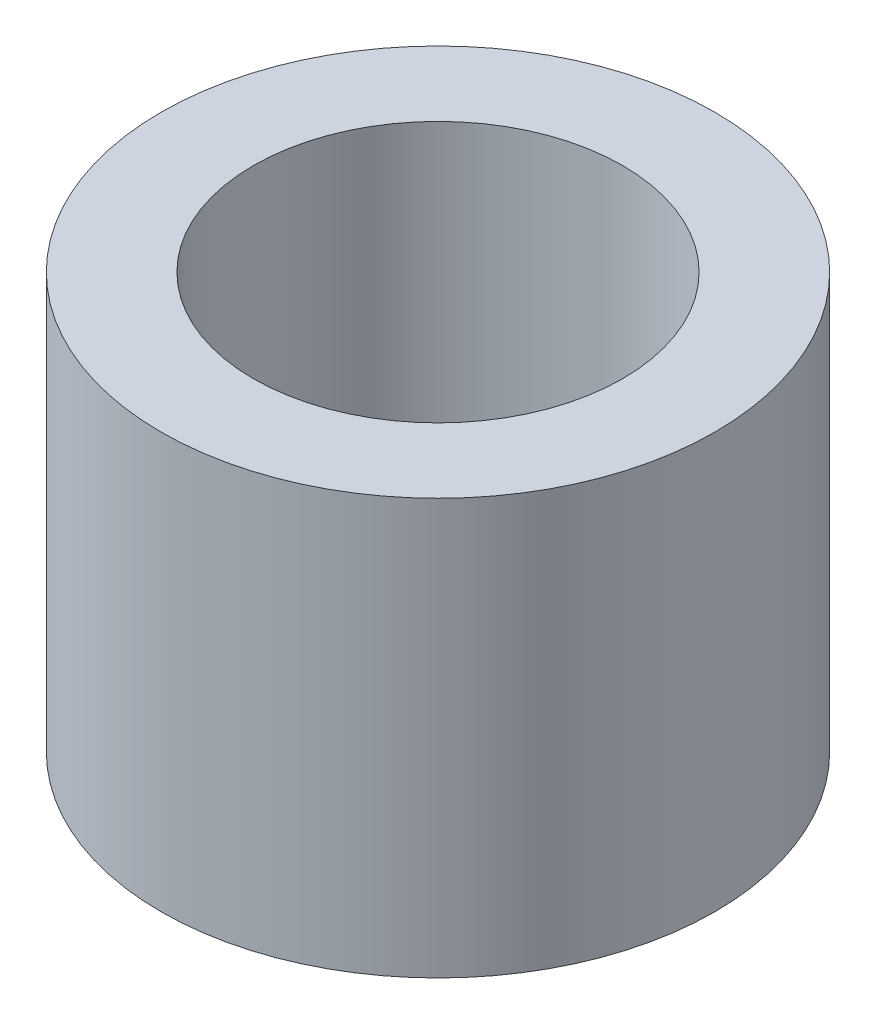
SolidWorks part; units mm, degrees
ref_plane "Front Plane" through (0, 0, 0) normal (0, 0, 1) x (1, 0, 0)
ref_plane "Top Plane" through (0, 0, 0) normal (0, 1, 0) x (1, 0, 0)
ref_plane "Right Plane" through (0, 0, 0) normal (1, 0, 0) x (0, 0, -1)
sketch "Sketch1" plane through (0, 0, 0) normal (0, 1, 0) x (1, 0, 0)
  circle A0 centre (0, 0) radius 3
  dimension "D1" = 6
extrude "Boss-Extrude1" add sketch "Sketch1" along normal blind 4.5
sketch "Sketch2" plane through (0, 4.5, 0) normal (0, 1, 0) x (1, 0, 0)
  circle A0 centre (0, 0) radius 2
  dimension "D1" = 4
extrude "Cut-Extrude1" cut sketch "Sketch2" against normal through all
